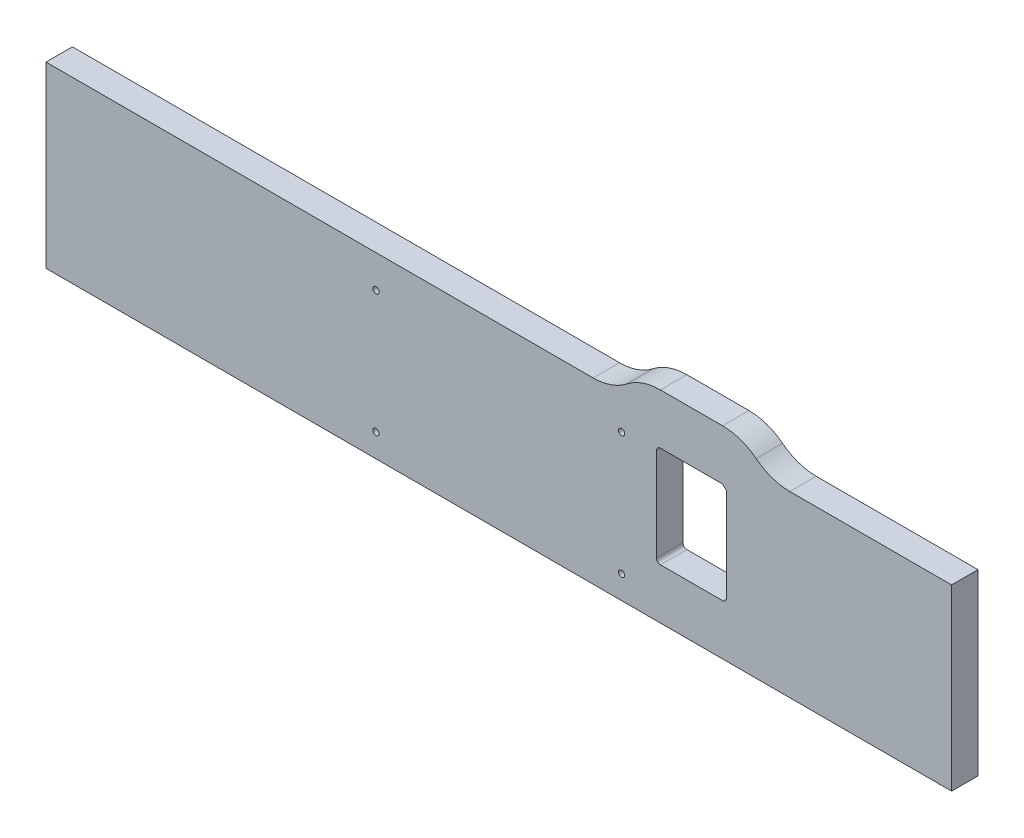
SolidWorks part; units mm, degrees
material "Pine"
ref_plane "Front Plane" through (0, 0, 0) normal (0, 0, 1) x (1, 0, 0)
ref_plane "Top Plane" through (0, 0, 0) normal (0, 1, 0) x (1, 0, 0)
ref_plane "Right Plane" through (0, 0, 0) normal (1, 0, 0) x (0, 0, -1)
sketch "Sketch1" plane through (0, 0, 0) normal (0, 0, 1) x (1, 0, 0)
  line L0 (-163.9887, -5335.905) -> (-163.9887, -5432.425)
  line L1 (-102.87, -5350.891) -> (-33.02, -5350.891)
  line L2 (-111.8235, -5341.9375) -> (-111.8235, -5334)
  line L3 (-24.0665, -5341.9375) -> (-24.0665, -5334)
  line L4 (-298.9262, -5332.73) -> (-167.1637, -5332.73)
  line L5 (-167.1637, -5435.6) -> (-298.9262, -5435.6)
  line L6 (-302.1012, -5432.425) -> (-302.1012, -5335.905)
  line L7 (-107.6325, -5329.809) -> (-28.2575, -5329.809)
  line L8 (174.9425, -5308.6) -> (174.9425, -5581.65)
  line L9 (449.2625, -5413.1661) -> (449.2625, -5421.9659)
  line L10 (595.3125, -5421.9659) -> (595.3125, -5413.1661)
  line L11 (839.47, -5509.5521) -> (839.47, -5307.6729)
  line L12 (839.47, -5307.6729) -> (863.6, -5307.6729)
  line L13 (839.47, -5509.5521) -> (863.6, -5509.5521)
  line L14 (863.6, -5509.5521) -> (863.6, -5307.6729)
  line L15 (-354.2665, -5341.9375) -> (-354.2665, -5334)
  line L16 (-100.8856, -5889.625) -> (-50.0856, -5889.625)
  line L17 (-104.0606, -5969) -> (-104.0606, -5892.8)
  line L18 (-46.9106, -5892.8) -> (-46.9106, -5969)
  line L19 (-50.0856, -5972.175) -> (-100.8856, -5972.175)
  line L20 (-100.8856, -5848.35) -> (-50.0856, -5848.35)
  line L21 (857.25, -5502.275) -> (157.1625, -5575.3)
  line L22 (857.25, -5314.95) -> (857.25, -5502.275)
  line L23 (157.1625, -5314.95) -> (157.1625, -5575.3)
  line L24 (857.25, -5314.95) -> (157.1625, -5314.95)
  line L25 (150.8125, -5308.6) -> (174.9425, -5308.6)
  line L26 (174.9425, -5581.65) -> (150.8125, -5581.65)
  line L27 (137.16, -5314.95) -> (137.16, -5502.275)
  line L28 (150.8125, -5581.65) -> (150.8125, -5308.6)
  line L29 (590.8224, -5408.676) -> (453.7526, -5408.676)
  line L30 (453.7526, -5426.456) -> (590.8224, -5426.456)
  line L31 (137.16, -6013.45) -> (137.16, -5867.4)
  line L32 (150.8125, -5746.75) -> (150.8125, -6019.8)
  line L33 (143.51, -5639.9938) -> (143.51, -5654.294)
  line L34 (590.8224, -5919.724) -> (453.7526, -5919.724)
  line L35 (453.7526, -5901.944) -> (590.8224, -5901.944)
  line L36 (449.2625, -5915.2339) -> (449.2625, -5906.4341)
  line L37 (174.9425, -6019.8) -> (174.9425, -5746.75)
  line L38 (595.3125, -5906.4341) -> (595.3125, -5915.2339)
  line L39 (839.47, -5818.8479) -> (839.47, -6020.7271)
  line L40 (839.47, -5818.8479) -> (863.6, -5818.8479)
  line L41 (863.6, -5818.8479) -> (863.6, -6020.7271)
  line L42 (839.47, -6020.7271) -> (863.6, -6020.7271)
  line L43 (-155.8782, -5867.4) -> (-603.25, -5867.4)
  line L44 (-433.07, -5350.891) -> (-363.22, -5350.891)
  line L45 (-437.8325, -5329.809) -> (-358.4575, -5329.809)
  line L46 (889, -6045.2) -> (-635, -6045.2)
  line L47 (-635, -5283.2) -> (889, -5283.2)
  line L48 (-635, -6045.2) -> (-635, -5283.2)
  line L49 (889, -5283.2) -> (889, -6045.2)
  line L50 (137.16, -5502.275) -> (-603.25, -5502.275)
  line L51 (-603.25, -5314.95) -> (137.16, -5314.95)
  line L52 (143.51, -5654.294) -> (-609.6, -5654.294)
  line L53 (-609.6, -5639.9938) -> (143.51, -5639.9938)
  line L54 (137.16, -5536.0062) -> (-603.25, -5536.0062)
  line L55 (-603.25, -5794.375) -> (137.16, -5794.375)
  line L56 (-603.25, -6013.45) -> (137.16, -6013.45)
  line L57 (-603.25, -5536.0062) -> (-603.25, -5794.375)
  line L58 (137.16, -5794.375) -> (137.16, -5536.0062)
  line L59 (-609.6, -5654.294) -> (-609.6, -5639.9938)
  line L60 (-603.25, -5867.4) -> (-603.25, -6013.45)
  line L61 (-603.25, -5314.95) -> (-603.25, -5502.275)
  line L62 (-442.0235, -5341.9375) -> (-442.0235, -5334)
  line L63 (857.25, -5826.125) -> (157.1625, -5753.1)
  line L64 (857.25, -6013.45) -> (857.25, -5826.125)
  line L65 (157.1625, -6013.45) -> (157.1625, -5753.1)
  line L66 (857.25, -6013.45) -> (157.1625, -6013.45)
  line L67 (174.9425, -5746.75) -> (150.8125, -5746.75)
  line L68 (150.8125, -6019.8) -> (174.9425, -6019.8)
  line L69 (137.16, -5867.4) -> (4.907, -5867.4)
  circle A0 centre (-36.195, -5484.0124) radius 1.5875
  arc A1 (-298.9262, -5332.73) -> (-302.1012, -5335.905) centre (-298.9262, -5335.905) ccw
  arc A2 (-302.1012, -5432.425) -> (-298.9262, -5435.6) centre (-298.9262, -5432.425) ccw
  arc A3 (-163.9887, -5335.905) -> (-167.1637, -5332.73) centre (-167.1637, -5335.905) ccw
  arc A4 (-167.1637, -5435.6) -> (-163.9887, -5432.425) centre (-167.1637, -5432.425) ccw
  arc A5 (-111.8235, -5341.9375) -> (-102.87, -5350.891) centre (-102.87, -5341.9375) ccw
  arc A6 (-107.6325, -5329.809) -> (-111.8235, -5334) centre (-107.6325, -5334) ccw
  circle A7 centre (166.0525, -5444.6613) radius 1.5875
  circle A8 centre (166.0525, -5358.1871) radius 1.5875
  circle A9 centre (471.4875, -5417.566) radius 1.5875
  arc A10 (453.7526, -5408.676) -> (449.2625, -5413.1661) centre (451.5076, -5410.9211) ccw
  arc A11 (449.2625, -5421.9659) -> (453.7526, -5426.456) centre (451.5076, -5424.2109) ccw
  circle A12 centre (522.2875, -5417.566) radius 1.5875
  circle A13 centre (573.0875, -5417.566) radius 1.5875
  arc A14 (590.8224, -5426.456) -> (595.3125, -5421.9659) centre (593.0674, -5424.2109) ccw
  arc A15 (595.3125, -5413.1661) -> (590.8224, -5408.676) centre (593.0674, -5410.9211) ccw
  circle A16 centre (848.36, -5471.8269) radius 1.5875
  circle A17 centre (848.36, -5409.0762) radius 1.5875
  circle A18 centre (848.36, -5346.3254) radius 1.5875
  arc A19 (-363.22, -5350.891) -> (-354.2665, -5341.9375) centre (-363.22, -5341.9375) ccw
  arc A20 (-354.2665, -5334) -> (-358.4575, -5329.809) centre (-358.4575, -5334) ccw
  arc A21 (-24.0665, -5334) -> (-28.2575, -5329.809) centre (-28.2575, -5334) ccw
  arc A22 (-33.02, -5350.891) -> (-24.0665, -5341.9375) centre (-33.02, -5341.9375) ccw
  circle A23 centre (-86.995, -5484.0124) radius 1.5875
  circle A24 centre (-333.4544, -5894.07) radius 2.54
  circle A25 centre (-333.4544, -5994.4) radius 2.54
  arc A26 (-104.0606, -5969) -> (-100.8856, -5972.175) centre (-100.8856, -5969) ccw
  arc A27 (-50.0856, -5972.175) -> (-46.9106, -5969) centre (-50.0856, -5969) ccw
  arc A28 (-100.8856, -5848.35) -> (-128.3819, -5857.875) centre (-100.8856, -5892.8) ccw
  arc A29 (-155.8782, -5867.4) -> (-128.3819, -5857.875) centre (-155.8782, -5822.95) ccw
  arc A30 (-22.5893, -5857.875) -> (-50.0856, -5848.35) centre (-50.0856, -5892.8) ccw
  circle A31 centre (-132.6356, -5894.07) radius 2.54
  circle A32 centre (-132.6356, -5994.4) radius 2.54
  arc A33 (-46.9106, -5892.8) -> (-50.0856, -5889.625) centre (-50.0856, -5892.8) ccw
  arc A34 (-100.8856, -5889.625) -> (-104.0606, -5892.8) centre (-100.8856, -5892.8) ccw
  arc A35 (-22.5893, -5857.875) -> (4.907, -5867.4) centre (4.907, -5822.95) ccw
  circle A36 centre (166.0525, -5531.1356) radius 1.5875
  arc A37 (449.2625, -5915.2339) -> (453.7526, -5919.724) centre (451.5076, -5917.4789) ccw
  arc A38 (453.7526, -5901.944) -> (449.2625, -5906.4341) centre (451.5076, -5904.1891) ccw
  circle A39 centre (166.0525, -5797.2644) radius 1.5875
  circle A40 centre (166.0525, -5883.7387) radius 1.5875
  circle A41 centre (166.0525, -5970.2129) radius 1.5875
  circle A42 centre (471.4875, -5910.834) radius 1.5875
  circle A43 centre (522.2875, -5910.834) radius 1.5875
  circle A44 centre (573.0875, -5910.834) radius 1.5875
  arc A45 (595.3125, -5906.4341) -> (590.8224, -5901.944) centre (593.0674, -5904.1891) ccw
  arc A46 (590.8224, -5919.724) -> (595.3125, -5915.2339) centre (593.0674, -5917.4789) ccw
  circle A47 centre (848.36, -5919.3238) radius 1.5875
  circle A48 centre (848.36, -5982.0746) radius 1.5875
  circle A49 centre (848.36, -5856.5731) radius 1.5875
  arc A50 (-437.8325, -5329.809) -> (-442.0235, -5334) centre (-437.8325, -5334) ccw
  circle A51 centre (-429.895, -5484.0124) radius 1.5875
  arc A52 (-442.0235, -5341.9375) -> (-433.07, -5350.891) centre (-433.07, -5341.9375) ccw
  circle A53 centre (-379.095, -5484.0124) radius 1.5875
sketch "Sketch2" plane through (0, 0, 0) normal (0, 0, 1) x (1, 0, 0)
  line L0 (137.16, -6013.45) -> (-603.25, -6013.45)
  line L1 (-603.25, -6013.45) -> (-603.25, -5867.4)
  line L2 (-603.25, -5867.4) -> (-155.8782, -5867.4)
  line L3 (-100.8856, -5848.35) -> (-50.0856, -5848.35)
  line L4 (4.907, -5867.4) -> (137.16, -5867.4)
  line L5 (137.16, -5867.4) -> (137.16, -6013.45)
  arc A0 (-155.8782, -5867.4) -> (-128.3819, -5857.875) centre (-155.8782, -5822.95) ccw
  arc A1 (-128.3819, -5857.875) -> (-100.8856, -5848.35) centre (-100.8856, -5892.8) cw
  arc A2 (-50.0856, -5848.35) -> (-22.5893, -5857.875) centre (-50.0856, -5892.8) cw
  arc A3 (-22.5893, -5857.875) -> (4.907, -5867.4) centre (4.907, -5822.95) ccw
extrude "Extrude1" add sketch "Sketch2" against normal blind 21.59
sketch "Sketch3" plane through (0, 0, 0) normal (0, 0, 1) x (1, 0, 0)
  line L0 (-104.0606, -5892.8) -> (-104.0606, -5969)
  line L1 (-100.8856, -5972.175) -> (-50.0856, -5972.175)
  line L2 (-46.9106, -5969) -> (-46.9106, -5892.8)
  line L3 (-46.9106, -5892.8) -> (-50.0856, -5889.625)
  line L4 (-50.0856, -5889.625) -> (-100.8856, -5889.625)
  circle A0 centre (-333.4544, -5994.4) radius 2.54
  circle A1 centre (-132.6356, -5994.4) radius 2.54
  circle A2 centre (-132.6356, -5894.07) radius 2.54
  circle A3 centre (-333.4544, -5894.07) radius 2.54
  arc A4 (-104.0606, -5969) -> (-100.8856, -5972.175) centre (-100.8856, -5969) ccw
  arc A5 (-50.0856, -5972.175) -> (-46.9106, -5969) centre (-50.0856, -5969) ccw
  arc A6 (-100.8856, -5889.625) -> (-104.0606, -5892.8) centre (-100.8856, -5892.8) ccw
extrude "Cut-Extrude1" cut sketch "Sketch3" against normal up to surface (21.59 mm away) up to face at (-138.5094, -5890.895, -21.59)
